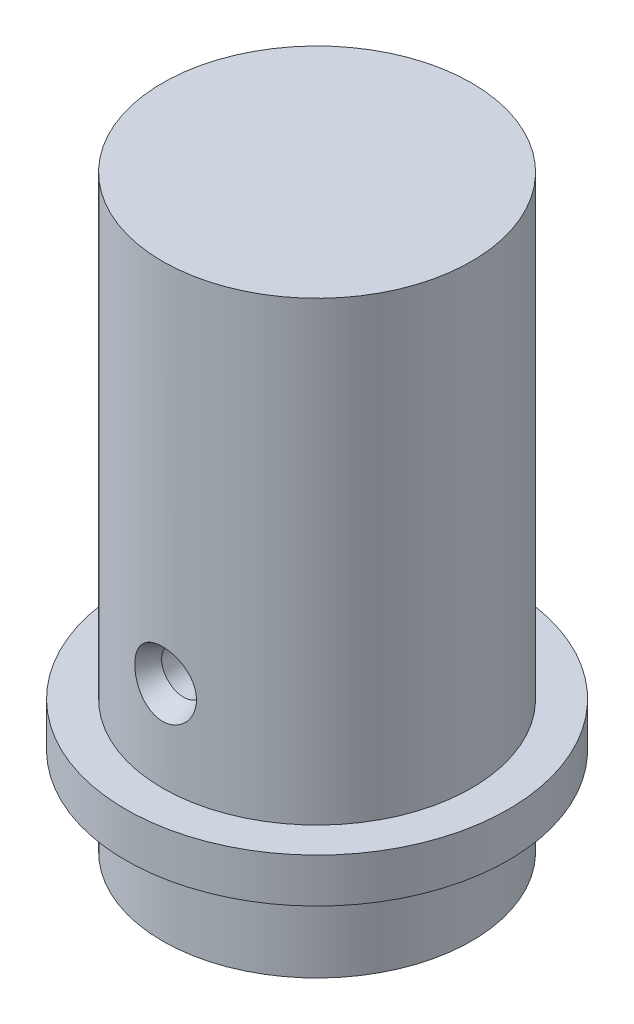
SolidWorks part; units mm, degrees
ref_plane "Front Plane" through (0, 0, 0) normal (0, 0, 1) x (1, 0, 0)
ref_plane "Top Plane" through (0, 0, 0) normal (0, 1, 0) x (1, 0, 0)
ref_plane "Right Plane" through (0, 0, 0) normal (1, 0, 0) x (0, 0, -1)
sketch "Sketch1" plane through (0, 0, 0) normal (0, 1, 0) x (1, 0, 0)
  circle A1 centre (0, 0) radius 10.5
extrude "Extrude1" add sketch "Sketch1" along normal blind 40
sketch "Sketch2" plane through (0, 0, 0) normal (0, -1, 0) x (1, 0, 0)
  circle A0 centre (0, 0) radius 2.5
extrude "Extrude2" cut sketch "Sketch2" against normal blind 22.5
ref_plane "Plane1" through (0, 6, 0) normal (0, -1, 0) x (1, 0, 0)
sketch "Sketch3" plane through (0, 6, 0) normal (0, -1, 0) x (1, 0, 0)
  circle A0 centre (0, 0) radius 13
  circle A1 centre (0, 0) radius 10.5
extrude "Extrude3" add sketch "Sketch3" against normal blind 3
sketch "Sketch4" plane through (0, 0, 0) normal (0, 0, 1) x (1, 0, 0)
  circle A1 centre (0, 15.1317) radius 1.5
extrude "Cut-Extrude1" cut sketch "Sketch4" against normal mid plane 28
ref_plane "Plane2" through (0, 24.5, 10.5) normal (0, 0, 1) x (-1, 0, 0)
sketch "Sketch7" plane through (0, 24.5, 10.5) normal (0, 0, 1) x (-1, 0, 0)
  circle A1 centre (0, 9.3683) radius 2.2
extrude "Cut-Extrude2" cut sketch "Sketch7" against normal blind 1.5 draft 26
ref_plane "Plane3" through (0, 0, -10.5) normal (0, 0, 1) x (1, 0, 0)
sketch "Sketch8" plane through (0, 0, -10.5) normal (0, 0, 1) x (1, 0, 0)
  circle A1 centre (0, 15.1317) radius 2.2
extrude "Cut-Extrude3" cut sketch "Sketch8" along normal blind 1.5 draft 26
